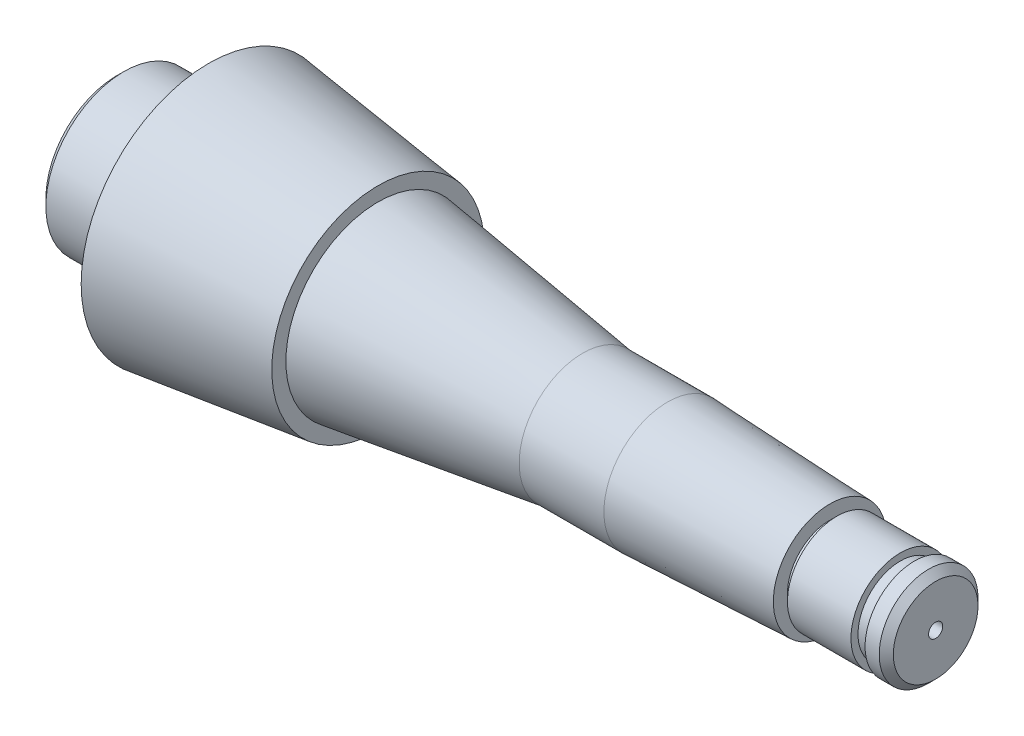
SolidWorks part; units mm, degrees
ref_plane "Plan de face" through (0, 0, 0) normal (0, 0, 1) x (1, 0, 0)
ref_plane "Plan de dessus" through (0, 0, 0) normal (0, 1, 0) x (1, 0, 0)
ref_plane "Plan de droite" through (0, 0, 0) normal (1, 0, 0) x (0, 0, -1)
sketch "Esquisse1" plane through (0, 0, 0) normal (0, 0, 1) x (1, 0, 0)
  line L0 (15.9892, 0) -> (-53.8011, 0) construction
  line L1 (116, 6) -> (115, 7)
  line L2 (115, 7) -> (113, 7)
  line L3 (113, 7) -> (113, 6)
  line L4 (113, 6) -> (111, 6)
  line L5 (111, 6) -> (111, 7)
  line L6 (0, 8.0555) -> (0, 10.0555)
  line L7 (0, 10.0555) -> (1, 11.0555)
  line L8 (1, 11.0555) -> (13, 11.0555)
  line L9 (13, 11.0555) -> (13, 18.0555)
  line L10 (13, 18.0555) -> (37, 15.0555)
  line L11 (37, 15.0555) -> (37, 13.0555)
  line L12 (37, 13.0555) -> (66, 9)
  line L13 (66, 9) -> (78, 9)
  line L14 (111, 7) -> (102, 7)
  line L15 (102, 7) -> (102, 6)
  line L16 (102, 6) -> (101, 6)
  line L17 (101, 6) -> (101, 8)
  line L18 (116, 1) -> (79, 1)
  line L19 (79, 1) -> (79, 0.75)
  line L20 (79, 0.75) -> (78.5, 0.75)
  line L21 (78.5, 0.75) -> (78.5, 0.5)
  line L22 (78.5, 0.5) -> (66, 0.5)
  line L23 (78, 9) -> (101, 8)
  line L24 (116, 6) -> (116, 1)
  line L25 (36, 1) -> (65, 1)
  line L26 (65, 1) -> (66, 0.5)
  line L30 (36, 1) -> (33, 4)
  line L31 (33, 4) -> (23, 4)
  line L32 (23, 4) -> (0, 8.0555)
  dimension "D1" = 4
  dimension "D2" = 12
  dimension "D3" = 1
  dimension "D4" = 45
  dimension "D5" = 2
  dimension "D6" = 170
  dimension "D7" = 23
  dimension "D8" = 7
  dimension "D9" = 24
  dimension "D10" = 3
  dimension "D11" = 9
  dimension "D12" = 2
  dimension "D13" = 10
  dimension "D14" = 3
  dimension "D15" = 1
  dimension "D16" = 2
  dimension "D17" = 2
  dimension "D18" = 1
  dimension "D19" = 1.5
  dimension "D20" = 1
  dimension "D21" = 37
  dimension "D22" = 0.5
  dimension "D23" = 9
  dimension "D24" = 12
  dimension "D25" = 23
  dimension "D26" = 29
  dimension "D27" = 2
  dimension "D28" = 1
  dimension "D29" = 29
  dimension "D30" = 2
  dimension "D31" = 5
  dimension "D32" = 135
  dimension "D33" = 1
  dimension "D34" = 1
  dimension "D35" = 2
revolve "Révolution1" add sketch "Esquisse1" angle 360 about L0
